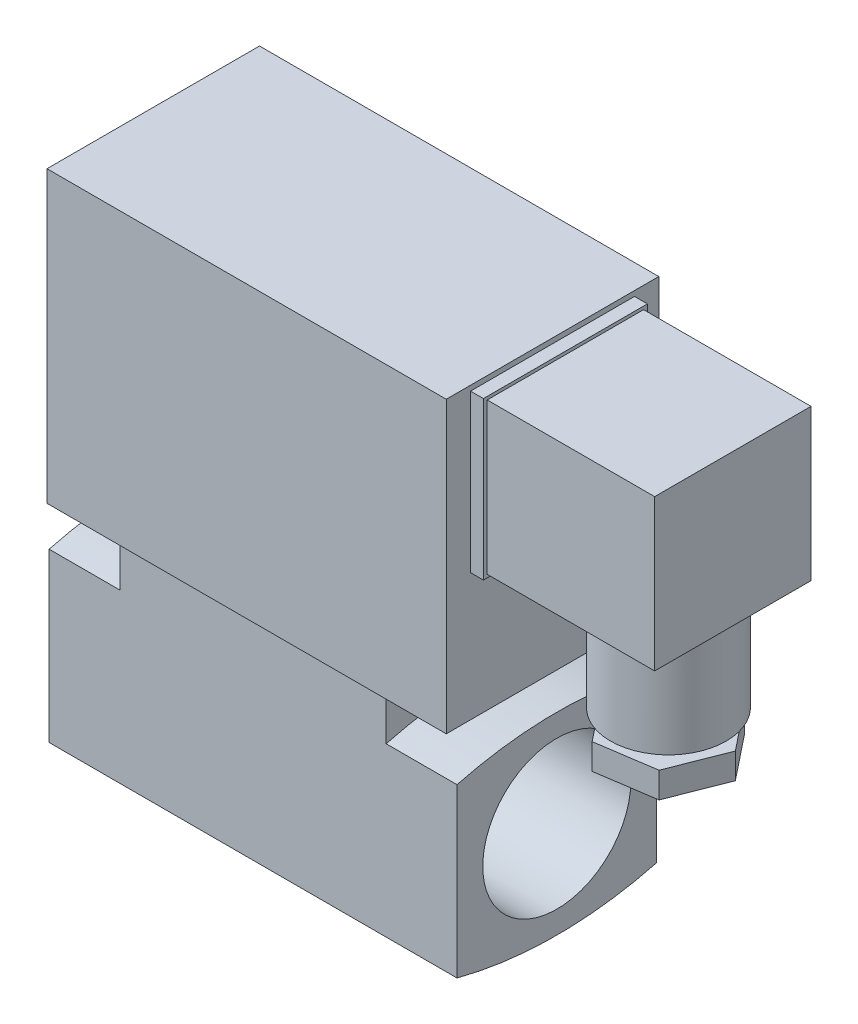
SolidWorks part; units mm, degrees
ref_plane "Alzado" through (0, 0, 0) normal (0, 0, 1) x (1, 0, 0)
ref_plane "Planta" through (0, 0, 0) normal (0, 1, 0) x (1, 0, 0)
ref_plane "Vista lateral" through (0, 0, 0) normal (1, 0, 0) x (0, 0, -1)
sketch "Croquis1" plane through (0, 0, 0) normal (0, 0, 1) x (1, 0, 0)
  line L1 (0, 0) -> (62, 0)
  line L2 (0, 0) -> (0, -45)
  line L3 (0, -45) -> (62, -45)
  line L4 (62, 0) -> (62, -45)
  dimension "D1" = 62
  dimension "D2" = 45
extrude "Saliente-Extruir1" add sketch "Croquis1" along normal blind 33
sketch "Croquis2" plane through (62, 0, 0) normal (1, 0, 0) x (0, 0, -1)
  line L0 (-16.5, 0) -> (-16.5, -13) construction
  line L1 (-33, 0) -> (0, 0) construction
  line L3 (-29.232, -25.2054) -> (-3.768, -25.2054)
  line L4 (-29.232, -25.2054) -> (-29.232, -0.7946)
  line L5 (-29.232, -0.7946) -> (-3.768, -0.7946)
  line L6 (-3.768, -25.2054) -> (-3.768, -0.7946)
  line L7 (-29.232, -25.2054) -> (-3.768, -0.7946) construction
  line L8 (-29.232, -0.7946) -> (-3.768, -25.2054) construction
  dimension "D1" = 13
extrude "Saliente-Extruir2" add sketch "Croquis2" along normal blind 2
sketch "Croquis3" plane through (64, 0, 0) normal (1, 0, 0) x (0, 0, -1)
  line L0 (-16.5, -0.7946) -> (-16.5, -13) construction
  line L1 (-3.768, -0.7946) -> (-29.232, -0.7946) construction
  line L2 (-16.5, -13) -> (-3.768, -13) construction
  line L3 (-3.768, -25.2054) -> (-3.768, -0.7946) construction
  line L5 (-4.359, -24.7219) -> (-28.641, -24.7219)
  line L6 (-4.359, -24.7219) -> (-4.359, -1.2781)
  line L7 (-4.359, -1.2781) -> (-28.641, -1.2781)
  line L8 (-28.641, -24.7219) -> (-28.641, -1.2781)
  line L9 (-4.359, -24.7219) -> (-28.641, -1.2781) construction
  line L10 (-4.359, -1.2781) -> (-28.641, -24.7219) construction
extrude "Saliente-Extruir3" add sketch "Croquis3" along normal blind 26
sketch "Croquis5" plane through (0, -45, 0) normal (0, -1, 0) x (1, 0, 0)
  line L0 (31, 33) -> (31, 0) construction
  line L1 (0, 33) -> (62, 33) construction
  line L2 (0, 0) -> (62, 0) construction
  line L4 (10.3332, 1) -> (51.6668, 1)
  line L5 (10.3332, 1) -> (10.3332, 32)
  line L6 (10.3332, 32) -> (51.6668, 32)
  line L7 (51.6668, 1) -> (51.6668, 32)
  line L8 (10.3332, 1) -> (51.6668, 32) construction
  line L9 (10.3332, 32) -> (51.6668, 1) construction
  point P6 (31, 16.5)
  dimension "D1" = 31
extrude "Saliente-Extruir5" add sketch "Croquis5" along normal blind 35
sketch "Croquis6" plane through (51.6668, 0, 0) normal (1, 0, 0) x (0, 0, -1)
  line L0 (-1, -80) -> (-1, -45) construction
  line L1 (-32, -80) -> (-1, -80)
  line L2 (-32, -80) -> (-32, -50)
  line L3 (-32, -50) -> (-1, -50)
  line L4 (-1, -80) -> (-1, -50)
  dimension "D1" = 30
extrude "Saliente-Extruir6" add sketch "Croquis6" along normal blind 11
sketch "Croquis7" plane through (10.3332, 0, 0) normal (-1, 0, 0) x (0, 0, 1)
  line L1 (1, -80) -> (32, -80)
  line L2 (1, -80) -> (1, -50)
  line L3 (1, -50) -> (32, -50)
  line L4 (32, -80) -> (32, -50)
extrude "Saliente-Extruir7" add sketch "Croquis7" along normal blind 11
sketch "Croquis8" plane through (62.6668, 0, 0) normal (1, 0, 0) x (0, 0, -1)
  line L0 (-32, -80) -> (-32, -78)
  line L1 (-32, -52) -> (-33.7231, -49.9313)
  line L2 (-32, -50) -> (-32, -80) construction
  line L3 (-32, -80) -> (-24.9866, -83.9868)
  line L4 (-1, -80) -> (-1, -50) construction
  line L5 (-1, -78) -> (-32, -78) construction
  line L6 (-33.7231, -49.9313) -> (-34.2253, -47.7885)
  line L7 (-24.9866, -83.9868) -> (-8.6959, -84.2794)
  line L8 (-8.6959, -84.2794) -> (-0.2741, -81.9934)
  line L9 (-32, -65) -> (-1, -65) construction
  line L10 (-1, -52) -> (-32, -52) construction
  line L11 (-0.2741, -81.9934) -> (0.929, -80.475)
  line L12 (-1, -52) -> (-32, -52) construction
  line L13 (-34.2253, -47.7885) -> (-30.9053, -47.3116)
  line L14 (-30.9053, -47.3116) -> (-17.9515, -46.7254)
  line L15 (-17.9515, -46.7254) -> (-10.1332, -47.3116)
  line L16 (-10.1332, -47.3116) -> (0, -48.0715)
  line L17 (0, -48.0715) -> (0, -49)
  line L18 (0, -49) -> (-1, -52)
  line L19 (0.929, -80.475) -> (-1, -78)
  arc A0 (-32, -78) -> (-1, -78) centre (-16.5, -18.9375) ccw
  arc A1 (-1, -52) -> (-32, -52) centre (-16.5, -111.0625) ccw
  dimension "D1" = 2
extrude "Cortar-Extruir1" cut sketch "Croquis8" against normal blind 11
sketch "Croquis9" plane through (51.6668, 0, 0) normal (1, 0, 0) x (0, 0, -1)
  line L0 (-32, -78) -> (-33.4976, -80)
  line L1 (-33.4976, -80) -> (-33.4976, -82.887)
  line L2 (-33.4976, -82.887) -> (-32, -84.3846)
  line L3 (-32, -84.3846) -> (-22.5752, -85.7125)
  line L4 (-22.5752, -85.7125) -> (-14.3518, -85.7125)
  line L5 (-14.3518, -85.7125) -> (-8.5322, -85.0485)
  line L6 (-8.5322, -85.0485) -> (-1, -84.3846)
  line L7 (-1, -84.3846) -> (0.7692, -82.6154)
  line L8 (0.7692, -82.6154) -> (1.4624, -80.4832)
  line L9 (1.4624, -80.4832) -> (1.4624, -79)
  line L10 (1.4624, -79) -> (-1, -78)
  arc A0 (-32, -78) -> (-1, -78) centre (-16.5, -18.9375) ccw
extrude "Cortar-Extruir2" cut sketch "Croquis9" against normal up to surface (52.3336 mm away) up to face at (-0.6668, -65, 16.5)
sketch "Croquis10" plane through (-0.6668, 0, 0) normal (-1, 0, 0) x (0, 0, 1)
  line L0 (32, -52) -> (34.1515, -49.263)
  line L1 (34.1515, -49.263) -> (33.0757, -47.196)
  line L2 (33.0757, -47.196) -> (22.5835, -46.6883)
  line L3 (22.5835, -46.6883) -> (7.099, -47.6312)
  line L4 (7.099, -47.6312) -> (-1.0965, -48.2295)
  line L5 (-1.0965, -48.2295) -> (1, -52)
  arc A0 (32, -52) -> (1, -52) centre (16.5, -111.0625) ccw
extrude "Cortar-Extruir3" cut sketch "Croquis10" against normal up to surface (11 mm away) up to face at (10.3332, -47.5, 16.5)
sketch "Croquis17" plane through (0, -24.7219, 0) normal (0, -1, 0) x (1, 0, 0)
  line L0 (90, 16.5) -> (80, 16.5) construction
  line L1 (90, 28.641) -> (90, 4.359) construction
  circle A0 centre (80, 16.5) radius 9
  dimension "D2" = 18
  dimension "D1" = 10
extrude "Saliente-Extruir8" add sketch "Croquis17" along normal blind 16
sketch "Croquis18" plane through (0, -40.7219, 0) normal (0, -1, 0) x (1, 0, 0)
  circle A0 centre (80, 16.5) radius 5.6252
extrude "Saliente-Extruir9" add sketch "Croquis18" along normal blind 2
sketch "Croquis19" plane through (0, -42.7219, 0) normal (0, -1, 0) x (1, 0, 0)
  line L1 (89.0329, 15.1451) -> (85.6899, 23.6453)
  line L2 (85.6899, 23.6453) -> (76.657, 25.0002)
  line L3 (76.657, 25.0002) -> (70.9671, 17.8549)
  line L4 (70.9671, 17.8549) -> (74.3101, 9.3547)
  line L5 (74.3101, 9.3547) -> (83.343, 7.9998)
  line L6 (83.343, 7.9998) -> (89.0329, 15.1451)
  circle A0 centre (80, 16.5) radius 7.9103 construction
extrude "Saliente-Extruir10" add sketch "Croquis19" along normal blind 4
sketch "Croquis20" plane through (62.6668, 0, 0) normal (1, 0, 0) x (0, 0, -1)
  line L0 (-16.5, -50) -> (-16.5, -80) construction
  arc A4 (-1, -52) -> (-32, -52) centre (-16.5, -111.0625) ccw construction
  arc A5 (-32, -78) -> (-1, -78) centre (-16.5, -18.9375) ccw construction
  circle A6 centre (-16.5, -65) radius 11.5
  dimension "D1" = 23
extrude "Cortar-Extruir6" cut sketch "Croquis20" against normal up to surface (63.3336 mm away) up to face at (-0.6668, -65, 16.5)
